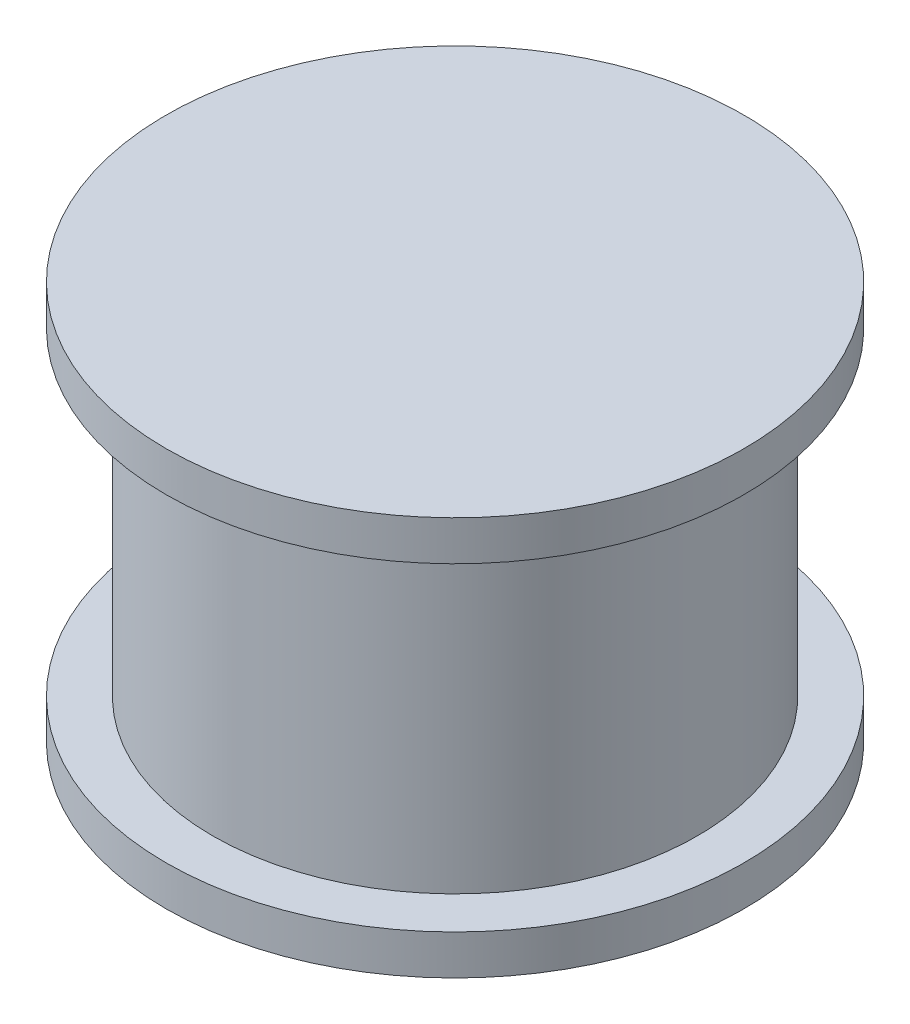
SolidWorks part; units mm, degrees
material "AISI 304"
ref_plane "Front Plane" through (0, 0, 0) normal (0, 0, 1) x (1, 0, 0)
ref_plane "Top Plane" through (0, 0, 0) normal (0, 1, 0) x (1, 0, 0)
ref_plane "Right Plane" through (0, 0, 0) normal (1, 0, 0) x (0, 0, -1)
sketch "Sketch1" plane through (0, 0, 0) normal (0, 1, 0) x (1, 0, 0)
  circle A0 centre (0, 0) radius 14.5
  dimension "D1" = 29
extrude "Boss-Extrude1" add sketch "Sketch1" along normal blind 2
sketch "Sketch2" plane through (0, 2, 0) normal (0, 1, 0) x (1, 0, 0)
  circle A0 centre (0, 0) radius 12.16
  dimension "D1" = 24.32
extrude "Boss-Extrude2" add sketch "Sketch2" along normal blind 16
sketch "Sketch3" plane through (0, 18, 0) normal (0, 1, 0) x (1, 0, 0)
  circle A0 centre (0, 0) radius 14.5
  dimension "D1" = 29
extrude "Boss-Extrude3" add sketch "Sketch3" along normal blind 2
